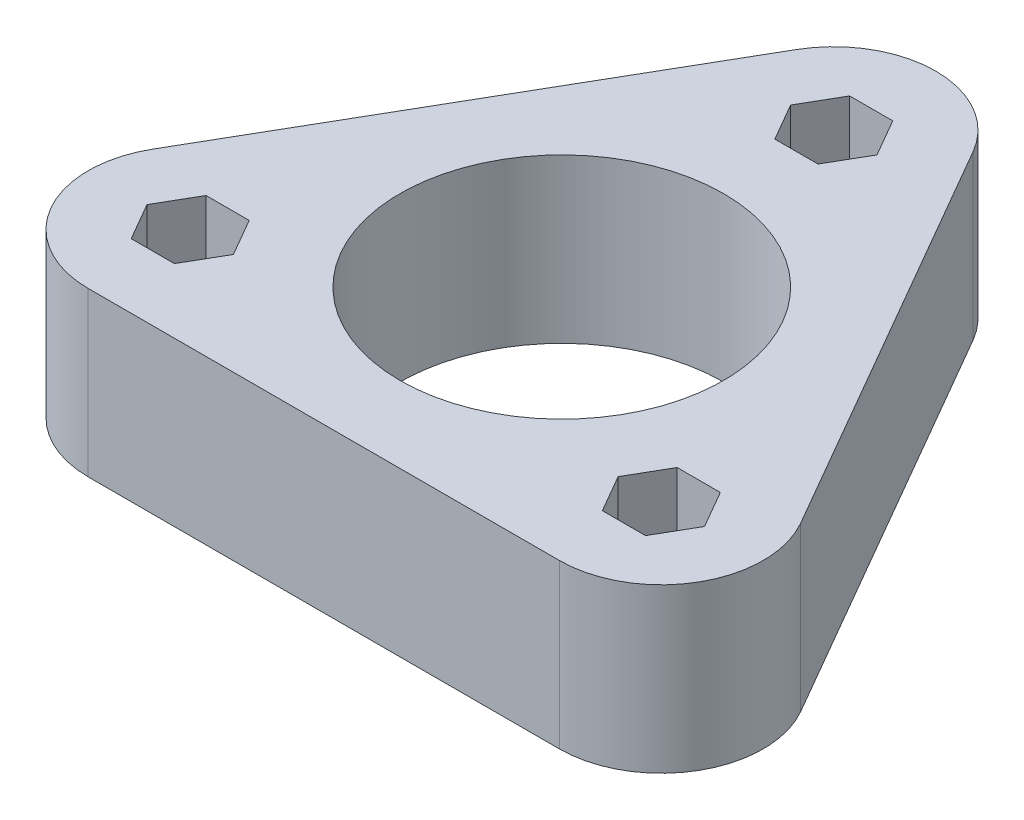
SolidWorks part; units mm, degrees
material "ABS"
ref_plane "Plan de face" through (0, 0, 0) normal (0, 0, 1) x (1, 0, 0)
ref_plane "Plan de dessus" through (0, 0, 0) normal (0, 1, 0) x (1, 0, 0)
ref_plane "Plan de droite" through (0, 0, 0) normal (1, 0, 0) x (0, 0, -1)
sketch "Esquisse1" plane through (0, 0, 0) normal (0, 1, 0) x (1, 0, 0)
  line L0 (-6.4952, 23.75) -> (-23.8157, -6.25)
  line L1 (-17.3205, -17.5) -> (17.3205, -17.5)
  line L2 (6.4952, 23.75) -> (23.8157, -6.25)
  line L3 (0, 20) -> (0, 0) construction
  line L4 (0, 0) -> (-17.3205, -10) construction
  line L6 (17.3205, -10) -> (0, 0) construction
  circle A0 centre (0, 0) radius 11.9
  circle A1 centre (-17.3205, -10) radius 1.5
  arc A2 (-23.8157, -6.25) -> (-17.3205, -17.5) centre (-17.3205, -10) ccw
  circle A3 centre (0, 20) radius 1.5
  circle A4 centre (17.3205, -10) radius 1.5
  circle A5 centre (0, 0) radius 16 construction
  arc A6 (17.3205, -17.5) -> (23.8157, -6.25) centre (17.3205, -10) ccw
  arc A7 (6.4952, 23.75) -> (-6.4952, 23.75) centre (0, 20) ccw
  circle A8 centre (0, 20) radius 4 construction
  dimension "D1" = 23.8
  dimension "D2" = 3
  dimension "D3" = 32
  dimension "D4" = 120
  dimension "D6" = 49.641
  dimension "D8" = 7.5
  dimension "D9" = 20
  dimension "D10" = 8
  dimension "D5" = 17.5
  dimension "D7" = 45
extrude "Boss.-Extru.1" add sketch "Esquisse1" along normal blind 12
sketch "Esquisse2" plane through (0, 12, 0) normal (0, 1, 0) x (1, 0, 0)
  line L0 (23.8157, -6.25) -> (6.4952, 23.75) construction
  line L1 (-18.9082, -7.25) -> (-20.4959, -10)
  line L2 (-20.4959, -10) -> (-18.9082, -12.75)
  line L3 (-18.9082, -12.75) -> (-15.7328, -12.75)
  line L4 (-15.7328, -12.75) -> (-14.1451, -10)
  line L5 (-14.1451, -10) -> (-15.7328, -7.25)
  line L6 (-15.7328, -7.25) -> (-18.9082, -7.25)
  line L7 (-1.5877, 22.75) -> (-3.1754, 20)
  line L8 (-3.1754, 20) -> (-1.5877, 17.25)
  line L9 (-1.5877, 17.25) -> (1.5877, 17.25)
  line L10 (1.5877, 17.25) -> (3.1754, 20)
  line L11 (3.1754, 20) -> (1.5877, 22.75)
  line L12 (1.5877, 22.75) -> (-1.5877, 22.75)
  line L13 (18.9082, -7.25) -> (15.7328, -7.25)
  line L14 (15.7328, -7.25) -> (14.1451, -10)
  line L15 (14.1451, -10) -> (15.7328, -12.75)
  line L16 (15.7328, -12.75) -> (18.9082, -12.75)
  line L17 (18.9082, -12.75) -> (20.4959, -10)
  line L18 (20.4959, -10) -> (18.9082, -7.25)
  line L19 (-6.4952, 23.75) -> (-23.8157, -6.25) construction
  circle A0 centre (-17.3205, -10) radius 2.75 construction
  circle A1 centre (0, 20) radius 2.75 construction
  circle A2 centre (17.3205, -10) radius 2.75 construction
  dimension "D1" = 5.5
extrude "Enlèv. mat.-Extru.1" cut sketch "Esquisse2" against normal blind 5
